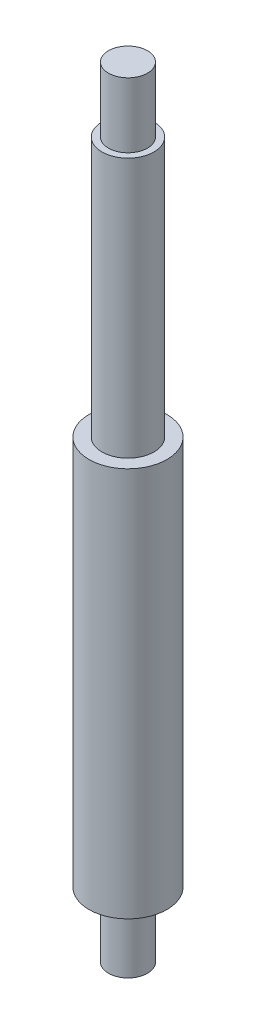
SolidWorks part; units mm, degrees
ref_plane "前视基准面" through (0, 0, 0) normal (0, 0, 1) x (1, 0, 0)
ref_plane "上视基准面" through (0, 0, 0) normal (0, 1, 0) x (1, 0, 0)
ref_plane "右视基准面" through (0, 0, 0) normal (1, 0, 0) x (0, 0, -1)
sketch "草图1" plane through (0, 0, 0) normal (0, 1, 0) x (1, 0, 0)
  circle A0 centre (0, 0) radius 3
  dimension "D1" = 6
extrude "凸台-拉伸1" add sketch "草图1" along normal blind 10
sketch "草图7" plane through (0, 10, 0) normal (0, 1, 0) x (1, 0, 0)
  circle A0 centre (0, 0) radius 6
  dimension "D1" = 12
extrude "凸台-拉伸2" add sketch "草图7" along normal blind 60
sketch "草图8" plane through (0, 70, 0) normal (0, 1, 0) x (1, 0, 0)
  circle A0 centre (0, 0) radius 4
  dimension "D1" = 8
extrude "凸台-拉伸3" add sketch "草图8" along normal blind 40
sketch "草图9" plane through (0, 110, 0) normal (0, 1, 0) x (-1, 0, 0)
  circle A0 centre (0, 0) radius 3
  dimension "D1" = 6
extrude "凸台-拉伸4" add sketch "草图9" along normal blind 10
